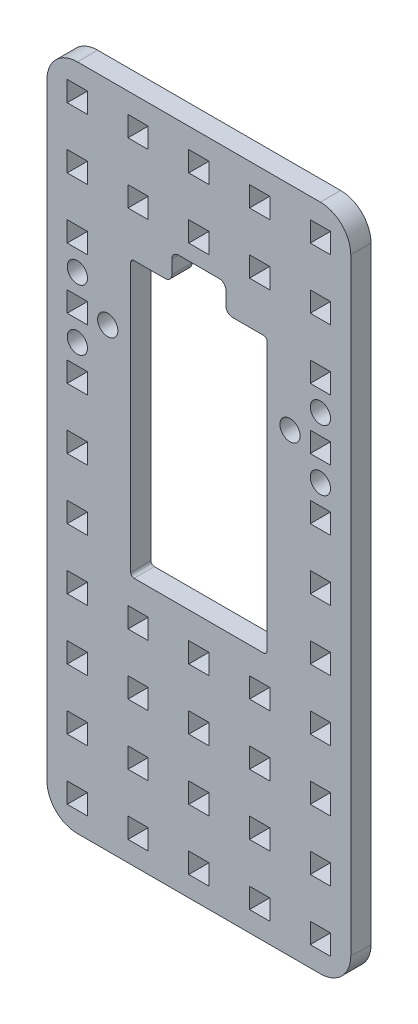
SolidWorks part; units mm, degrees
ref_plane "Alzado" through (0, 0, 0) normal (0, 0, 1) x (1, 0, 0)
ref_plane "Planta" through (0, 0, 0) normal (0, 1, 0) x (1, 0, 0)
ref_plane "Vista lateral" through (0, 0, 0) normal (1, 0, 0) x (0, 0, -1)
sketch "Model" plane through (0, 0, 0) normal (0, 0, 1) x (1, 0, 0)
  line L0 (51.1085, 295.4985) -> (48.1085, 295.4985)
  line L1 (51.1085, 292.4985) -> (51.1085, 295.4985)
  line L2 (48.1085, 292.4985) -> (51.1085, 292.4985)
  line L3 (48.1085, 295.4985) -> (48.1085, 292.4985)
  line L4 (51.1085, 286.4985) -> (48.1085, 286.4985)
  line L5 (51.1085, 283.4985) -> (51.1085, 286.4985)
  line L6 (48.1085, 283.4985) -> (51.1085, 283.4985)
  line L7 (48.1085, 286.4985) -> (48.1085, 283.4985)
  line L8 (51.1085, 277.4985) -> (48.1085, 277.4985)
  line L9 (51.1085, 274.4985) -> (51.1085, 277.4985)
  line L10 (48.1085, 274.4985) -> (51.1085, 274.4985)
  line L11 (48.1085, 277.4985) -> (48.1085, 274.4985)
  line L12 (51.1085, 268.4985) -> (48.1085, 268.4985)
  line L13 (51.1085, 265.4985) -> (51.1085, 268.4985)
  line L14 (48.1085, 265.4985) -> (51.1085, 265.4985)
  line L15 (48.1085, 268.4985) -> (48.1085, 265.4985)
  line L16 (51.1085, 259.4985) -> (48.1085, 259.4985)
  line L17 (51.1085, 256.4985) -> (51.1085, 259.4985)
  line L18 (48.1085, 256.4985) -> (51.1085, 256.4985)
  line L19 (48.1085, 259.4985) -> (48.1085, 256.4985)
  line L20 (51.1085, 250.4985) -> (48.1085, 250.4985)
  line L21 (51.1085, 247.4985) -> (51.1085, 250.4985)
  line L22 (48.1085, 247.4985) -> (51.1085, 247.4985)
  line L23 (48.1085, 250.4985) -> (48.1085, 247.4985)
  line L24 (51.1085, 241.4985) -> (48.1085, 241.4985)
  line L25 (51.1085, 238.4985) -> (51.1085, 241.4985)
  line L26 (48.1085, 238.4985) -> (51.1085, 238.4985)
  line L27 (48.1085, 241.4985) -> (48.1085, 238.4985)
  line L28 (51.1085, 232.4985) -> (48.1085, 232.4985)
  line L29 (51.1085, 229.4985) -> (51.1085, 232.4985)
  line L30 (48.1085, 229.4985) -> (51.1085, 229.4985)
  line L31 (48.1085, 232.4985) -> (48.1085, 229.4985)
  line L32 (51.1085, 223.4985) -> (48.1085, 223.4985)
  line L33 (51.1085, 220.4985) -> (51.1085, 223.4985)
  line L34 (48.1085, 220.4985) -> (51.1085, 220.4985)
  line L35 (48.1085, 223.4985) -> (48.1085, 220.4985)
  line L36 (51.1085, 214.4985) -> (48.1085, 214.4985)
  line L37 (51.1085, 211.4985) -> (51.1085, 214.4985)
  line L38 (48.1085, 211.4985) -> (51.1085, 211.4985)
  line L39 (48.1085, 214.4985) -> (48.1085, 211.4985)
  line L40 (51.1085, 205.4985) -> (48.1085, 205.4985)
  line L41 (51.1085, 202.4985) -> (51.1085, 205.4985)
  line L42 (48.1085, 202.4985) -> (51.1085, 202.4985)
  line L43 (48.1085, 205.4985) -> (48.1085, 202.4985)
  line L44 (15.1085, 295.4985) -> (12.1085, 295.4985)
  line L45 (15.1085, 292.4985) -> (15.1085, 295.4985)
  line L46 (12.1085, 292.4985) -> (15.1085, 292.4985)
  line L47 (12.1085, 295.4985) -> (12.1085, 292.4985)
  line L48 (15.1085, 286.4985) -> (12.1085, 286.4985)
  line L49 (15.1085, 283.4985) -> (15.1085, 286.4985)
  line L50 (12.1085, 283.4985) -> (15.1085, 283.4985)
  line L51 (12.1085, 286.4985) -> (12.1085, 283.4985)
  line L52 (15.1085, 277.4985) -> (12.1085, 277.4985)
  line L53 (15.1085, 274.4985) -> (15.1085, 277.4985)
  line L54 (12.1085, 274.4985) -> (15.1085, 274.4985)
  line L55 (12.1085, 277.4985) -> (12.1085, 274.4985)
  line L56 (15.1085, 268.4985) -> (12.1085, 268.4985)
  line L57 (15.1085, 265.4985) -> (15.1085, 268.4985)
  line L58 (12.1085, 265.4985) -> (15.1085, 265.4985)
  line L59 (12.1085, 268.4985) -> (12.1085, 265.4985)
  line L60 (15.1085, 259.4985) -> (12.1085, 259.4985)
  line L61 (15.1085, 256.4985) -> (15.1085, 259.4985)
  line L62 (12.1085, 256.4985) -> (15.1085, 256.4985)
  line L63 (12.1085, 259.4985) -> (12.1085, 256.4985)
  line L64 (15.1085, 250.4985) -> (12.1085, 250.4985)
  line L65 (15.1085, 247.4985) -> (15.1085, 250.4985)
  line L66 (12.1085, 247.4985) -> (15.1085, 247.4985)
  line L67 (12.1085, 250.4985) -> (12.1085, 247.4985)
  line L68 (15.1085, 241.4985) -> (12.1085, 241.4985)
  line L69 (15.1085, 238.4985) -> (15.1085, 241.4985)
  line L70 (12.1085, 238.4985) -> (15.1085, 238.4985)
  line L71 (12.1085, 241.4985) -> (12.1085, 238.4985)
  line L72 (15.1085, 232.4985) -> (12.1085, 232.4985)
  line L73 (15.1085, 229.4985) -> (15.1085, 232.4985)
  line L74 (12.1085, 229.4985) -> (15.1085, 229.4985)
  line L75 (12.1085, 232.4985) -> (12.1085, 229.4985)
  line L76 (15.1085, 223.4985) -> (12.1085, 223.4985)
  line L77 (15.1085, 220.4985) -> (15.1085, 223.4985)
  line L78 (12.1085, 220.4985) -> (15.1085, 220.4985)
  line L79 (12.1085, 223.4985) -> (12.1085, 220.4985)
  line L80 (15.1085, 214.4985) -> (12.1085, 214.4985)
  line L81 (15.1085, 211.4985) -> (15.1085, 214.4985)
  line L82 (12.1085, 211.4985) -> (15.1085, 211.4985)
  line L83 (12.1085, 214.4985) -> (12.1085, 211.4985)
  line L84 (15.1085, 205.4985) -> (12.1085, 205.4985)
  line L85 (15.1085, 202.4985) -> (15.1085, 205.4985)
  line L86 (12.1085, 202.4985) -> (15.1085, 202.4985)
  line L87 (12.1085, 205.4985) -> (12.1085, 202.4985)
  line L88 (42.1085, 205.4985) -> (39.1085, 205.4985)
  line L89 (42.1085, 202.4985) -> (42.1085, 205.4985)
  line L90 (39.1085, 202.4985) -> (42.1085, 202.4985)
  line L91 (39.1085, 205.4985) -> (39.1085, 202.4985)
  line L92 (24.1085, 205.4985) -> (21.1085, 205.4985)
  line L93 (24.1085, 202.4985) -> (24.1085, 205.4985)
  line L94 (21.1085, 202.4985) -> (24.1085, 202.4985)
  line L95 (21.1085, 205.4985) -> (21.1085, 202.4985)
  line L96 (33.1085, 205.4985) -> (30.1085, 205.4985)
  line L97 (33.1085, 202.4985) -> (33.1085, 205.4985)
  line L98 (30.1085, 202.4985) -> (33.1085, 202.4985)
  line L99 (30.1085, 205.4985) -> (30.1085, 202.4985)
  line L100 (42.1085, 223.4985) -> (39.1085, 223.4985)
  line L101 (42.1085, 220.4985) -> (42.1085, 223.4985)
  line L102 (39.1085, 220.4985) -> (42.1085, 220.4985)
  line L103 (39.1085, 223.4985) -> (39.1085, 220.4985)
  line L104 (24.1085, 223.4985) -> (21.1085, 223.4985)
  line L105 (24.1085, 220.4985) -> (24.1085, 223.4985)
  line L106 (21.1085, 220.4985) -> (24.1085, 220.4985)
  line L107 (21.1085, 223.4985) -> (21.1085, 220.4985)
  line L108 (33.1085, 223.4985) -> (30.1085, 223.4985)
  line L109 (33.1085, 220.4985) -> (33.1085, 223.4985)
  line L110 (30.1085, 220.4985) -> (33.1085, 220.4985)
  line L111 (30.1085, 223.4985) -> (30.1085, 220.4985)
  line L112 (42.1085, 214.4985) -> (39.1085, 214.4985)
  line L113 (42.1085, 211.4985) -> (42.1085, 214.4985)
  line L114 (39.1085, 211.4985) -> (42.1085, 211.4985)
  line L115 (39.1085, 214.4985) -> (39.1085, 211.4985)
  line L116 (24.1085, 214.4985) -> (21.1085, 214.4985)
  line L117 (24.1085, 211.4985) -> (24.1085, 214.4985)
  line L118 (21.1085, 211.4985) -> (24.1085, 211.4985)
  line L119 (21.1085, 214.4985) -> (21.1085, 211.4985)
  line L120 (33.1085, 214.4985) -> (30.1085, 214.4985)
  line L121 (33.1085, 211.4985) -> (33.1085, 214.4985)
  line L122 (30.1085, 211.4985) -> (33.1085, 211.4985)
  line L123 (30.1085, 214.4985) -> (30.1085, 211.4985)
  line L124 (42.1085, 295.4985) -> (39.1085, 295.4985)
  line L125 (42.1085, 292.4985) -> (42.1085, 295.4985)
  line L126 (39.1085, 292.4985) -> (42.1085, 292.4985)
  line L127 (39.1085, 295.4985) -> (39.1085, 292.4985)
  line L128 (24.1085, 295.4985) -> (21.1085, 295.4985)
  line L129 (24.1085, 292.4985) -> (24.1085, 295.4985)
  line L130 (21.1085, 292.4985) -> (24.1085, 292.4985)
  line L131 (21.1085, 295.4985) -> (21.1085, 292.4985)
  line L132 (33.1085, 295.4985) -> (30.1085, 295.4985)
  line L133 (33.1085, 292.4985) -> (33.1085, 295.4985)
  line L134 (30.1085, 292.4985) -> (33.1085, 292.4985)
  line L135 (30.1085, 295.4985) -> (30.1085, 292.4985)
  line L136 (42.1085, 286.4985) -> (39.1085, 286.4985)
  line L137 (42.1085, 283.4985) -> (42.1085, 286.4985)
  line L138 (39.1085, 283.4985) -> (42.1085, 283.4985)
  line L139 (39.1085, 286.4985) -> (39.1085, 283.4985)
  line L140 (24.1085, 286.4985) -> (21.1085, 286.4985)
  line L141 (24.1085, 283.4985) -> (24.1085, 286.4985)
  line L142 (21.1085, 283.4985) -> (24.1085, 283.4985)
  line L143 (21.1085, 286.4985) -> (21.1085, 283.4985)
  line L144 (42.1085, 232.4985) -> (39.1085, 232.4985)
  line L145 (42.1085, 229.4985) -> (42.1085, 232.4985)
  line L146 (39.1085, 229.4985) -> (42.1085, 229.4985)
  line L147 (39.1085, 232.4985) -> (39.1085, 229.4985)
  line L148 (24.1085, 232.4985) -> (21.1085, 232.4985)
  line L149 (24.1085, 229.4985) -> (24.1085, 232.4985)
  line L150 (21.1085, 229.4985) -> (24.1085, 229.4985)
  line L151 (21.1085, 232.4985) -> (21.1085, 229.4985)
  line L152 (33.1085, 232.4985) -> (30.1085, 232.4985)
  line L153 (33.1085, 229.4985) -> (33.1085, 232.4985)
  line L154 (30.1085, 229.4985) -> (33.1085, 229.4985)
  line L155 (30.1085, 232.4985) -> (30.1085, 229.4985)
  line L156 (33.1085, 286.4985) -> (30.1085, 286.4985)
  line L157 (33.1085, 283.4985) -> (33.1085, 286.4985)
  line L158 (30.1085, 283.4985) -> (33.1085, 283.4985)
  line L159 (30.1085, 286.4985) -> (30.1085, 283.4985)
  line L160 (13.6085, 199.4985) -> (49.6085, 199.4985)
  line L161 (54.1085, 203.9985) -> (54.1085, 293.9985)
  line L162 (49.6085, 298.4985) -> (13.6085, 298.4985)
  line L163 (9.1085, 293.9985) -> (9.1085, 203.9985)
  line L164 (21.5082, 276.6986) -> (21.5082, 236.9486)
  line L165 (26.6082, 277.1986) -> (22.0082, 277.1986)
  line L166 (41.7082, 236.9486) -> (41.7082, 276.6986)
  line L167 (41.2082, 277.1986) -> (36.6082, 277.1986)
  line L168 (27.6082, 278.1986) -> (27.6082, 280.1986)
  line L169 (35.6082, 278.1986) -> (35.6082, 280.1986)
  line L170 (28.6082, 281.1986) -> (34.6082, 281.1986)
  line L171 (22.0082, 236.4486) -> (41.2082, 236.4486)
  arc A0 (49.6085, 199.4985) -> (54.1085, 203.9985) centre (49.6085, 203.9985) ccw
  arc A1 (9.1085, 203.9985) -> (13.6085, 199.4985) centre (13.6085, 203.9985) ccw
  arc A2 (54.1085, 293.9985) -> (49.6085, 298.4985) centre (49.6085, 293.9985) ccw
  arc A3 (13.6085, 298.4985) -> (9.1085, 293.9985) centre (13.6085, 293.9985) ccw
  arc A4 (21.5082, 236.9486) -> (22.0082, 236.4486) centre (22.0082, 236.9486) ccw
  arc A5 (22.0082, 277.1986) -> (21.5082, 276.6986) centre (22.0082, 276.6986) ccw
  arc A6 (41.2082, 236.4486) -> (41.7082, 236.9486) centre (41.2082, 236.9486) ccw
  arc A7 (41.7082, 276.6986) -> (41.2082, 277.1986) centre (41.2082, 276.6986) ccw
  arc A8 (26.6082, 277.1986) -> (27.6082, 278.1986) centre (26.6082, 278.1986) ccw
  arc A9 (35.6082, 278.1986) -> (36.6082, 277.1986) centre (36.6082, 278.1986) ccw
  arc A10 (35.6082, 280.1986) -> (34.6082, 281.1986) centre (34.6082, 280.1986) ccw
  arc A11 (28.6082, 281.1986) -> (27.6082, 280.1986) centre (28.6082, 280.1986) ccw
  circle A12 centre (45.1085, 266.9985) radius 1.5
  circle A13 centre (18.1085, 266.9985) radius 1.5
  circle A14 centre (49.6085, 262.4985) radius 1.5
  circle A15 centre (49.6085, 271.4985) radius 1.5
  circle A16 centre (13.6085, 262.4985) radius 1.5
  circle A17 centre (13.6085, 271.4985) radius 1.5
extrude "Saliente-Extruir1" add sketch "Model" along normal blind 3
